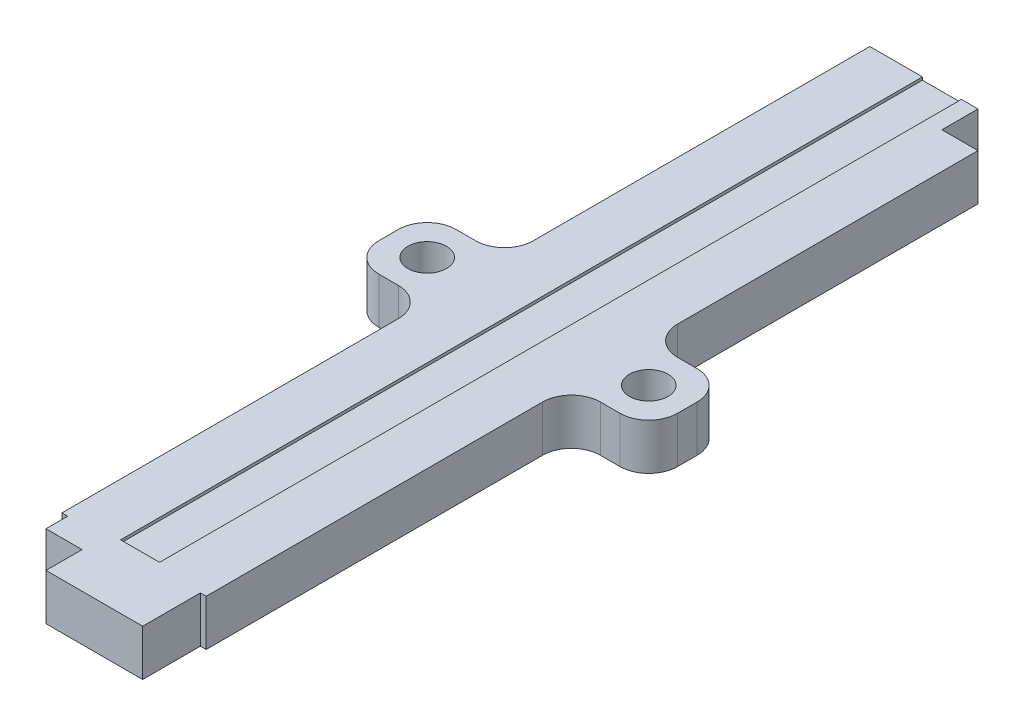
SolidWorks part; units mm, degrees
ref_plane "Front Plane" through (0, 0, 0) normal (0, 0, 1) x (1, 0, 0)
ref_plane "Top Plane" through (0, 0, 0) normal (0, 1, 0) x (1, 0, 0)
ref_plane "Right Plane" through (0, 0, 0) normal (1, 0, 0) x (0, 0, -1)
sketch "Sketch1" plane through (0, 0, 0) normal (0, 0, 1) x (1, 0, 0)
  line L1 (-6.35, -2.032) -> (6.35, -2.032)
  line L2 (-6.35, -2.032) -> (-6.35, 2.032)
  line L3 (-6.35, 2.032) -> (6.35, 2.032)
  line L4 (6.35, -2.032) -> (6.35, 2.032)
  line L5 (-6.35, -2.032) -> (6.35, 2.032) construction
  line L6 (-6.35, 2.032) -> (6.35, -2.032) construction
  point P0 (0, 0)
  dimension "D1" = 4.064
  dimension "D2" = 12.7
extrude "Boss-Extrude1" add sketch "Sketch1" along normal blind 228.6
sketch "Sketch2" plane through (0, 2.032, 0) normal (0, 1, 0) x (1, 0, 0)
  line L0 (1.7145, -114.3) -> (6.35, -114.3) construction
  line L1 (-1.7145, -5.6134) -> (1.7145, -5.6134)
  line L2 (-1.7145, -5.6134) -> (-1.7145, -222.9866)
  line L3 (-1.7145, -222.9866) -> (1.7145, -222.9866)
  line L4 (1.7145, -5.6134) -> (1.7145, -222.9866)
  line L5 (6.35, -228.6) -> (6.35, 0) construction
  line L6 (-1.7145, -114.3) -> (-6.35, -114.3) construction
  line L7 (-6.35, -228.6) -> (-6.35, 0) construction
  dimension "D1" = 3.429
  dimension "D2" = 217.3732
extrude "Cut-Extrude1" cut sketch "Sketch2" against normal blind 0.254
sketch "Sketch3" plane through (0, 2.032, 0) normal (0, 1, 0) x (1, 0, 0)
  line L1 (-6.35, -228.6) -> (-5.842, -228.6)
  line L2 (-6.35, -228.6) -> (-6.35, -223.52)
  line L3 (-6.35, -223.52) -> (-5.842, -223.52)
  line L4 (-5.842, -228.6) -> (-5.842, -223.52)
  dimension "D1" = 0.508
  dimension "D2" = 5.08
extrude "Cut-Extrude2" cut sketch "Sketch3" against normal through all
ref_plane "Plane1" through (0, 0, 114.3) normal (0, 0, -1) x (-1, 0, 0)
mirror "Mirror1" about plane through (0, 0, 114.3) normal (0, 0, -1) of "Cut-Extrude2"
mirror "Mirror2" about plane through (0, 0, 0) normal (1, 0, 0) of "Mirror1", "Cut-Extrude2"
sketch "Sketch4" plane through (0, 2.032, 0) normal (0, 1, 0) x (1, 0, 0)
  line L2 (-5.842, -228.6) -> (-2.667, -228.6)
  line L3 (-5.842, -228.6) -> (-5.842, -225.425)
  line L4 (-5.842, -225.425) -> (-2.667, -225.425)
  line L5 (-2.667, -228.6) -> (-2.667, -225.425)
  dimension "D1" = 3.175
  dimension "D2" = 3.175
extrude "Cut-Extrude3" cut sketch "Sketch4" against normal through all
sketch "Sketch5" plane through (0, 2.032, 0) normal (0, 1, 0) x (1, 0, 0)
  line L0 (5.842, 0) -> (-5.842, 0) construction
  line L1 (-6.35, 0) -> (6.35, 0)
  line L2 (-6.35, 0) -> (-6.35, -152.4)
  line L3 (-6.35, -152.4) -> (6.35, -152.4) construction
  line L4 (6.35, 0) -> (6.35, -152.4)
  line L5 (5.842, -228.6) -> (-2.667, -228.6) construction
  line L6 (-6.35, -223.52) -> (-6.35, -5.08) construction
  line L7 (6.35, -223.52) -> (6.35, -5.08) construction
  line L8 (-6.35, -152.4) -> (3.175, -152.4)
  line L9 (3.175, -152.4) -> (3.175, -155.575)
  line L10 (3.175, -155.575) -> (6.35, -155.575)
  line L11 (6.35, -155.575) -> (6.35, -152.4)
  dimension "D1" = 0
  dimension "D2" = 76.2
  dimension "D3" = 0
  dimension "D4" = 0
  dimension "D5" = 3.175
  dimension "D6" = 3.175
extrude "Cut-Extrude4" cut sketch "Sketch5" against normal through all
sketch "Sketch7" plane through (0, 2.032, 0) normal (0, 1, 0) x (1, 0, 0)
  line L0 (-13.1521, -187.96) -> (-9.7511, -187.96) construction
  line L1 (-6.35, -223.52) -> (-6.35, -152.4) construction
  line L2 (0, -152.4) -> (0, -222.9866) construction
  line L3 (-13.1521, -184.5589) -> (-6.35, -184.5589)
  line L4 (-13.1521, -184.5589) -> (-13.1521, -191.3611)
  line L5 (-13.1521, -191.3611) -> (-6.35, -191.3611)
  line L6 (-6.35, -184.5589) -> (-6.35, -191.3611)
  line L7 (-1.7145, -152.4) -> (1.7145, -152.4) construction
  line L8 (-1.7145, -222.9866) -> (1.7145, -222.9866) construction
  line L9 (-13.1521, -184.5589) -> (-6.35, -184.5589)
  line L10 (-13.1521, -191.3611) -> (-6.35, -191.3611)
  line L11 (6.35, -223.52) -> (6.35, -155.575) construction
  line L12 (13.1521, -191.3611) -> (6.35, -191.3611)
  line L13 (13.1521, -184.5589) -> (6.35, -184.5589)
  line L14 (6.35, -184.5589) -> (6.35, -191.3611)
  line L15 (13.1521, -191.3611) -> (6.35, -191.3611)
  line L16 (13.1521, -184.5589) -> (13.1521, -191.3611)
  line L17 (13.1521, -184.5589) -> (6.35, -184.5589)
  circle A0 centre (-9.7511, -187.96) radius 1.7005
  circle A1 centre (9.7511, -187.96) radius 1.7005
  line M1 (6.35, -223.52) -> (6.35, -155.575)
  line M9 (-6.35, -152.4) -> (-6.35, -223.52)
  dimension "D1" = 3.4011
  dimension "D2" = 6.8021
  dimension "D3" = 3.4011
  dimension "D4" = 31.6255
extrude "Boss-Extrude2" add sketch "Sketch7" against normal through all contours L16 L13 L12 A1 M1 | L4 L5 L3 A0 M9
fillet "Fillet1" radius 2.54 8 edges at (13.1521, 0, 191.3611) (13.1521, 0, 184.5589) (-13.1521, 0, 184.5589) (-13.1521, 0, 191.3611)
